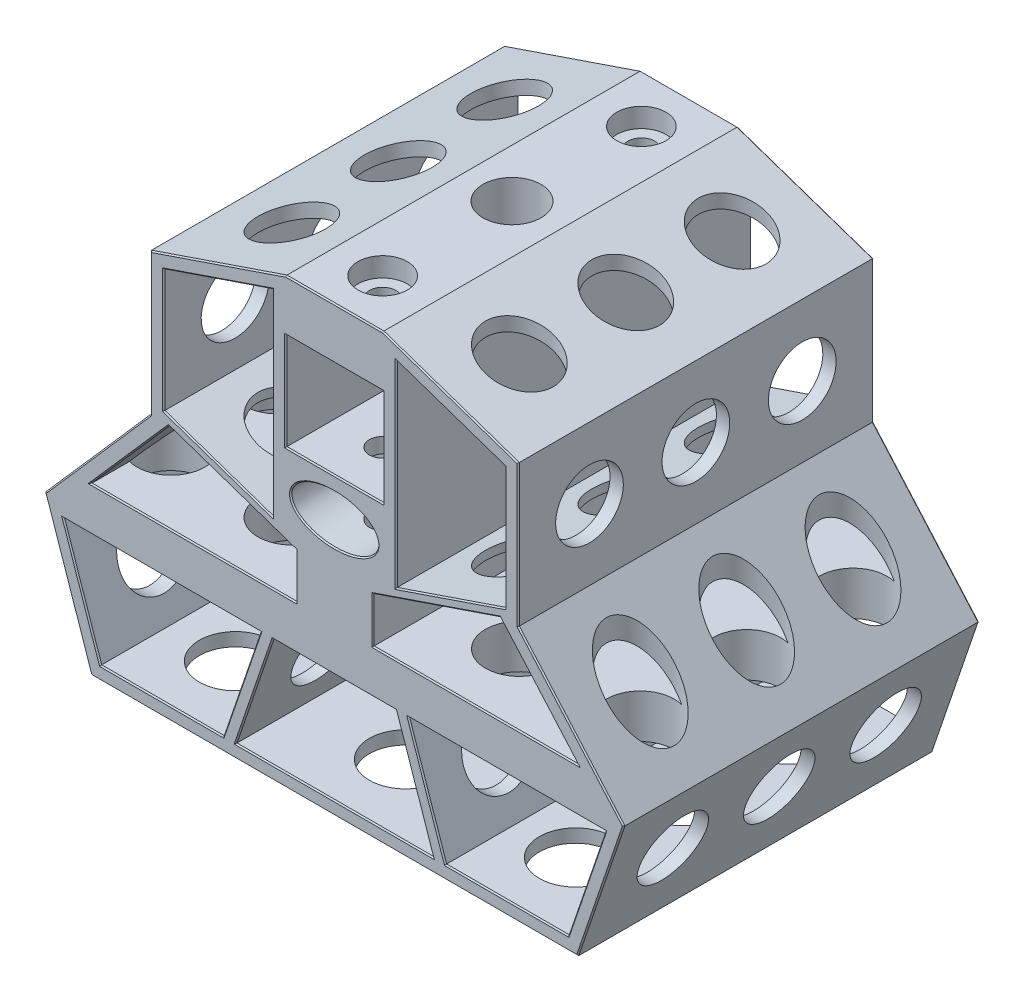
SolidWorks part; units mm, degrees
ref_plane "Front Plane" through (0, 0, 0) normal (0, 0, 1) x (1, 0, 0)
ref_plane "Top Plane" through (0, 0, 0) normal (0, 1, 0) x (1, 0, 0)
ref_plane "Right Plane" through (0, 0, 0) normal (1, 0, 0) x (0, 0, -1)
sketch "Sketch1" plane through (0, 0, 0) normal (0, 0, 1) x (1, 0, 0)
  line L0 (0, 45.5072) -> (0, -40.4348) construction
  line L1 (-48.8406, 0) -> (45.7971, 0) construction
  line L3 (10.0225, -10.0225) -> (-10.0225, -10.0225)
  line L4 (10.0225, -10.0225) -> (10.0225, 10.0225)
  line L5 (10.0225, 10.0225) -> (-10.0225, 10.0225)
  line L6 (-10.0225, -10.0225) -> (-10.0225, 10.0225)
  line L7 (10.0225, -10.0225) -> (-10.0225, 10.0225) construction
  line L8 (10.0225, 10.0225) -> (-10.0225, -10.0225) construction
  line L18 (-12.5, -46.0225) -> (12.5, -46.0225)
  line L19 (12.5, -46.0225) -> (20, -68.0225)
  line L20 (-20, -68.0225) -> (20, -68.0225)
  line L21 (-12.5, -46.0225) -> (-20, -68.0225)
  line L40 (15.6695, -46.0225) -> (23.1695, -68.0225)
  line L45 (15.6695, -46.0225) -> (55.6695, -46.0225)
  line L47 (55.6695, -46.0225) -> (48.1695, -68.0225)
  line L49 (48.1695, -68.0225) -> (23.1695, -68.0225)
  line L51 (59.8618, -43.0225) -> (50.3163, -71.0225)
  line L53 (-35.6695, -68.0225) -> (-35.6695, -75.9008) construction
  line L54 (15.6695, -43.0225) -> (59.8618, -43.0225) construction
  line L55 (-15.6695, -46.0225) -> (-55.6695, -46.0225)
  line L56 (14.6468, -43.0225) -> (24.1923, -71.0225) construction
  line L57 (-24.1923, -71.0225) -> (24.1923, -71.0225) construction
  line L58 (50.3163, -71.0225) -> (23.1695, -71.0225) construction
  line L59 (-55.6695, -46.0225) -> (-48.1695, -68.0225)
  line L60 (-48.1695, -68.0225) -> (-23.1695, -68.0225)
  line L61 (-15.6695, -46.0225) -> (-23.1695, -68.0225)
  line L62 (-14.6468, -43.0225) -> (-24.1923, -71.0225) construction
  line L64 (-59.8618, -43.0225) -> (-50.3163, -71.0225)
  line L67 (-11.4773, -43.0225) -> (-21.0227, -71.0225) construction
  line L68 (-11.4773, -43.0225) -> (-59.8618, -43.0225) construction
  line L69 (-14.6468, -43.0225) -> (14.6468, -43.0225) construction
  line L70 (-50.3163, -71.0225) -> (-21.0227, -71.0225) construction
  line L71 (-50.3163, -71.0225) -> (50.3163, -71.0225)
  line L72 (-13.0225, -23.5) -> (-13.0225, 16.5)
  line L73 (-13.0225, 16.5) -> (-35.0225, 9)
  line L74 (-35.0225, 9) -> (-35.0225, -16)
  line L75 (-35.0225, -16) -> (-13.0225, -23.5)
  line L76 (-39.4516, -3.5) -> (45.7971, -3.5) construction
  line L77 (35.0225, 9) -> (35.0225, -16)
  line L78 (13.0225, 16.5) -> (35.0225, 9)
  line L79 (13.0225, -23.5) -> (13.0225, 16.5)
  line L80 (35.0225, -16) -> (13.0225, -23.5)
  line L83 (-10.0225, 20.6923) -> (-38.0225, 11.1468)
  line L84 (-38.0225, 11.1468) -> (-38.0225, -18.1468)
  line L85 (-10.0225, -27.6923) -> (-10.0225, 20.6923) construction
  line L86 (-38.0225, -18.1468) -> (-10.0225, -27.6923) construction
  line L87 (-59.8618, -43.0225) -> (-38.0225, -18.1468)
  line L88 (-10.0225, 20.6923) -> (0, 20.6923)
  line L89 (38.0225, 11.1468) -> (38.0225, -18.1468)
  line L92 (10.0225, 20.6923) -> (38.0225, 11.1468)
  line L93 (10.0225, -27.6923) -> (10.0225, 20.6923) construction
  line L94 (38.0225, -18.1468) -> (10.0225, -27.6923) construction
  line L95 (59.8618, -43.0225) -> (38.0225, -18.1468)
  line L96 (10.0225, 20.6923) -> (0, 20.6923)
  point P5 (0, 0)
  point P10 (0, 0)
  point P13 (0, 14)
  point P14 (0, 35)
  point P16 (22.4772, 38)
  point P18 (-22.4772, 38)
  point P19 (0, 35)
  point P20 (-14.7629, 11)
  point P33 (14.7629, 11)
  dimension "D1" = 20.045
  dimension "D2" = 20.045
  dimension "D3" = 25
  dimension "D4" = 40
  dimension "D5" = 22
  dimension "D6" = 3
  dimension "D8" = 36
  dimension "D9" = 20
  dimension "D10" = 3
  dimension "D11" = 40
  dimension "D7" = 12.5
  dimension "D13" = 3
  dimension "D14" = 40
  dimension "D15" = 25
  dimension "D16" = 3.5
  dimension "D17" = 12.5
  dimension "D18" = 20
  dimension "D19" = 22
  dimension "D12" = 3
  dimension "D20" = 3
  dimension "D21" = 3
extrude "Boss-Extrude1" add sketch "Sketch1" along normal blind 73.5
sketch "Sketch2" plane through (0, 0, 0) normal (0, 0, 1) x (1, 0, 0)
  line L0 (-8, -27.3252) -> (-8, -36.7124)
  line L5 (0, 26.7053) -> (0, -60.761) construction
  line L14 (8, -27.3252) -> (8, -36.7124)
  line L15 (8, -36.7124) -> (50.3298, -36.7124)
  line L19 (-35.7681, -20.1261) -> (-57.6074, -45.0018)
  line L20 (-34.2361, -18.3811) -> (-50.3298, -36.7124)
  line L21 (-50.3298, -36.7124) -> (-8, -36.7124)
  line L22 (-35.6678, -17.893) -> (-13.6678, -25.393)
  line L23 (-34.2361, -18.3811) -> (-8, -27.3252)
  line L24 (34.2361, -18.3811) -> (50.3298, -36.7124)
  line L25 (34.2361, -18.3811) -> (8, -27.3252)
  dimension "D1" = 8
  dimension "D2" = 3
  dimension "D3" = 2
extrude "Cut-Extrude2" cut sketch "Sketch2" along normal through all
sketch "Sketch3" plane through (0, 0, 0) normal (0, 0, 1) x (1, 0, 0)
  line L0 (0, 24.4574) -> (0, -32.3369) construction
  ellipse E0 centre (0, -18) end of major axis (9, -18) minor radius 5
  dimension "D1" = 18
  dimension "D2" = 9
  dimension "D5" = 5
extrude "Cut-Extrude4" cut sketch "Sketch3" along normal through all
sketch "Sketch4" plane through (0, 0, 0) normal (1, 0, 0) x (0, 0, -1)
  line L0 (-89.3161, -56.52) -> (42.3095, -56.52) construction
  line L1 (-36.75, 29.8449) -> (-36.75, -56.0115) construction
  line L2 (-36.75, -56.52) -> (-58.75, -56.52) construction
  line L3 (-36.75, -56.52) -> (-14.75, -56.52) construction
  line L4 (-36.75, -56.52) -> (-14.75, -56.52) construction
  circle A0 centre (-36.75, -56.52) radius 7
  circle A2 centre (-58.75, -56.52) radius 7
  circle A3 centre (-14.75, -56.52) radius 7
  dimension "D3" = 14
  dimension "D1" = 56.52
  dimension "D2" = 36.75
  dimension "D5" = 22
  dimension "D7" = 22
  dimension "D6" = 2
  dimension "D4" = 2
extrude "Cut-Extrude5" cut sketch "Sketch4" against normal through all both and the other way through all
sketch "Sketch5" plane through (38.0225, 0, 0) normal (1, 0, 0) x (0, 0, -1)
  line L0 (-85.8813, -3.5) -> (19.6328, -3.5) construction
  line L1 (-36.75, -3.5) -> (-14.75, -3.5) construction
  line L2 (-36.75, -3.5) -> (-58.75, -3.5) construction
  circle A0 centre (-36.75, -3.5) radius 7
  circle A1 centre (-14.75, -3.5) radius 7
  circle A2 centre (-58.75, -3.5) radius 7
  dimension "D2" = 14
  dimension "D3" = 36.75
  dimension "D1" = 3.5
  dimension "D5" = 22
  dimension "D7" = 22
  dimension "D4" = 2
  dimension "D6" = 2
extrude "Cut-Extrude6" cut sketch "Sketch5" against normal blind 10
sketch "Sketch6" plane through (-38.0225, 0, 0) normal (-1, 0, 0) x (0, 0, 1)
  line L0 (-12.5672, -3.5) -> (85.8413, -3.5) construction
  line L1 (36.75, -3.5) -> (58.75, -3.5) construction
  line L2 (36.75, -3.5) -> (14.75, -3.5) construction
  circle A0 centre (36.75, -3.5) radius 7
  circle A1 centre (58.75, -3.5) radius 7
  circle A2 centre (14.75, -3.5) radius 7
  dimension "D2" = 14
  dimension "D3" = 36.75
  dimension "D1" = 3.5
  dimension "D5" = 22
  dimension "D7" = 22
  dimension "D4" = 2
  dimension "D6" = 2
extrude "Cut-Extrude7" cut sketch "Sketch6" against normal blind 10
sketch "Sketch7" plane through (0, -71.0225, 0) normal (0, -1, 0) x (1, 0, 0)
  line L0 (0, 77.452) -> (0, -13.4565) construction
  line L1 (0, 36.75) -> (35.16, 36.75) construction
  line L2 (0, 36.75) -> (-35.16, 36.75) construction
  circle A0 centre (0, 36.75) radius 7.5
  circle A1 centre (35.16, 36.75) radius 7.5
  circle A4 centre (-35.16, 36.75) radius 7.5
  circle A5 centre (0, 58.75) radius 7.5 [skipped]
  circle A6 centre (35.16, 58.75) radius 7.5 [skipped]
  circle A7 centre (0, 58.75) radius 7.5
  circle A8 centre (35.16, 58.75) radius 7.5
  circle A9 centre (-35.16, 58.75) radius 7.5
  circle A10 centre (0, 14.75) radius 7.5
  circle A11 centre (35.16, 14.75) radius 7.5
  circle A12 centre (-35.16, 14.75) radius 7.5
  dimension "D1" = 15
  dimension "D2" = 36.75
  dimension "D5" = 35.16
  dimension "D7" = 35.16
  dimension "D3" = 2
  dimension "D4" = 2
  dimension "D6" = 2
  dimension "D8" = 2
  dimension "D9" = 2
extrude "Cut-Extrude8" cut sketch "Sketch7" against normal blind 10
sketch "Sketch8" plane through (0, 0, 0) normal (0, 1, 0) x (1, 0, 0)
  line L0 (0, 9.1455) -> (0, -79.6194) construction
  circle A0 centre (23.52, -36.75) radius 7
  circle A1 centre (23.52, -14.75) radius 7
  circle A2 centre (23.52, -58.75) radius 7
  circle A3 centre (-23.52, -58.75) radius 7
  circle A4 centre (-23.52, -14.75) radius 7
  circle A5 centre (-23.52, -36.75) radius 7
  circle A6 centre (-48.52, -14.75) radius 7
  circle A7 centre (-48.52, -36.75) radius 7
  circle A8 centre (-48.52, -58.75) radius 7
  circle A9 centre (48.52, -14.75) radius 7
  circle A10 centre (48.52, -36.75) radius 7
  circle A11 centre (48.52, -58.75) radius 7
  dimension "D1" = 14
  dimension "D2" = 36.75
  dimension "D3" = 23.52
  dimension "D4" = 2
  dimension "D5" = 2
  dimension "D6" = 2
  dimension "D7" = 2
extrude "Cut-Extrude9" cut sketch "Sketch8" along normal through all and the other way up to surface other way up to face at (35.6695, -46.0225, 36.75)
sketch "Sketch9" plane through (0, 20.6923, 0) normal (0, 1, 0) x (1, 0, 0)
  line L0 (0, 10.7424) -> (0, -82.6878) construction
  line L1 (-69.9781, -36.75) -> (68.9694, -36.75) construction
  circle A0 centre (0, -10) radius 2.75
  circle A1 centre (0, -63.5) radius 2.75
  circle A3 centre (0, -36.75) radius 6
  point P5 (0, -10)
  dimension "D2" = 5.5
  dimension "D3" = 12
  dimension "D1" = 36.75
  dimension "D4" = 26.75
extrude "Cut-Extrude10" cut sketch "Sketch9" against normal up to surface (66.7148 mm away) up to face at (0, -46.0225, 36.75)
sketch "Sketch10" plane through (0, 20.6923, 0) normal (0, 1, 0) x (1, 0, 0)
  circle A0 centre (0, -10) radius 5.1
  circle A1 centre (0, -63.5) radius 5.1
  dimension "D1" = 10.2
  dimension "D2" = 10.2
extrude "Cut-Extrude11" cut sketch "Sketch10" against normal blind 4
sketch "Sketch11" plane through (0, 0, 0) normal (0, 0, 1) x (1, 0, 0)
  line L80 (-35.2725, -16.1789) -> (-12.7725, -23.8494)
  line L81 (-12.7725, -23.8494) -> (-12.7725, 16.8494)
  line L82 (-12.7725, 16.8494) -> (-35.2725, 9.1789)
  line L83 (-35.2725, 9.1789) -> (-35.2725, -16.1789)
  line L84 (35.2725, 9.1789) -> (35.2725, -16.1789)
  line L85 (35.2725, -16.1789) -> (12.7725, -23.8494)
  line L86 (12.7725, -23.8494) -> (12.7725, 16.8494)
  line L87 (12.7725, 16.8494) -> (35.2725, 9.1789)
  line L88 (15.3202, -45.7725) -> (22.9906, -68.2725)
  line L89 (48.3484, -68.2725) -> (22.9906, -68.2725)
  line L90 (56.0189, -45.7725) -> (48.3484, -68.2725)
  line L91 (15.3202, -45.7725) -> (56.0189, -45.7725)
  line L92 (-20.3494, -68.2725) -> (20.3494, -68.2725)
  line L93 (12.6789, -45.7725) -> (20.3494, -68.2725)
  line L94 (-12.6789, -45.7725) -> (12.6789, -45.7725)
  line L95 (-12.6789, -45.7725) -> (-20.3494, -68.2725)
  line L96 (-56.0189, -45.7725) -> (-48.3484, -68.2725)
  line L97 (-48.3484, -68.2725) -> (-22.9906, -68.2725)
  line L98 (-15.3202, -45.7725) -> (-22.9906, -68.2725)
  line L99 (-15.3202, -45.7725) -> (-56.0189, -45.7725)
extrude "Cut-Extrude19" cut sketch "Sketch11" along normal through all
chamfer "Chamfer1" distance 0.25 angle 45 86 edges at (9, -18, 0) (42.283, -27.5468, 0) (29.1649, -36.7124, 0) (8, -32.0188, 0) (21.118, -22.8532, 0) (0, 10.0225, 0) (10.0225, 0, 0) (0, -10.0225, 0) (-10.0225, 0, 0) (38.0225, -3.5, 0) (24.0225, 15.9195, 0) (0, 20.6923, 0) (-24.0225, 15.9195, 0) (-38.0225, -3.5, 0) (-48.9422, -30.5847, 0) (-55.0891, -57.0225, 0) (0, -71.0225, 0) (55.0891, -57.0225, 0) (48.9422, -30.5847, 0) (-8, -32.0188, 0) (-29.1649, -36.7124, 0) (-42.283, -27.5468, 0) (-21.118, -22.8532, 0) (9, -18, 73.5) (55.0891, -57.0225, 73.5) (0, -71.0225, 73.5) (-55.0891, -57.0225, 73.5) (-48.9422, -30.5847, 73.5) (-38.0225, -3.5, 73.5) (-24.0225, 15.9195, 73.5) (0, 20.6923, 73.5) (24.0225, 15.9195, 73.5) (38.0225, -3.5, 73.5) (48.9422, -30.5847, 73.5) (10.0225, 0, 73.5) (0, 10.0225, 73.5) (-10.0225, 0, 73.5) (0, -10.0225, 73.5) (29.1649, -36.7124, 73.5) (42.283, -27.5468, 73.5) (21.118, -22.8532, 73.5) (8, -32.0188, 73.5) (-29.1649, -36.7124, 73.5) (-8, -32.0188, 73.5) (-21.118, -22.8532, 73.5) (-42.283, -27.5468, 73.5) (24.0225, -20.0141, 0) (12.7725, -3.5, 0) (24.0225, 13.0141, 0) (35.2725, -3.5, 0) (-35.6695, -68.2725, 0) (-52.1837, -57.0225, 0) (-35.6695, -45.7725, 0) (-19.1554, -57.0225, 0) (-12.7725, -3.5, 0) (-24.0225, -20.0141, 0) (-35.2725, -3.5, 0) (-24.0225, 13.0141, 0) (16.5141, -57.0225, 0) (0, -68.2725, 0) (-16.5141, -57.0225, 0) (0, -45.7725, 0) (35.6695, -68.2725, 0) (19.1554, -57.0225, 0) (35.6695, -45.7725, 0) (52.1837, -57.0225, 0) (12.7725, -3.5, 73.5) (24.0225, -20.0141, 73.5) (35.2725, -3.5, 73.5) (24.0225, 13.0141, 73.5) (-52.1837, -57.0225, 73.5) (-35.6695, -68.2725, 73.5) (-19.1554, -57.0225, 73.5) (-35.6695, -45.7725, 73.5) (-24.0225, -20.0141, 73.5) (-12.7725, -3.5, 73.5) (-24.0225, 13.0141, 73.5) (-35.2725, -3.5, 73.5) (0, -68.2725, 73.5) (16.5141, -57.0225, 73.5) (0, -45.7725, 73.5) (-16.5141, -57.0225, 73.5) (19.1554, -57.0225, 73.5) (35.6695, -68.2725, 73.5) (52.1837, -57.0225, 73.5) (35.6695, -45.7725, 73.5)
